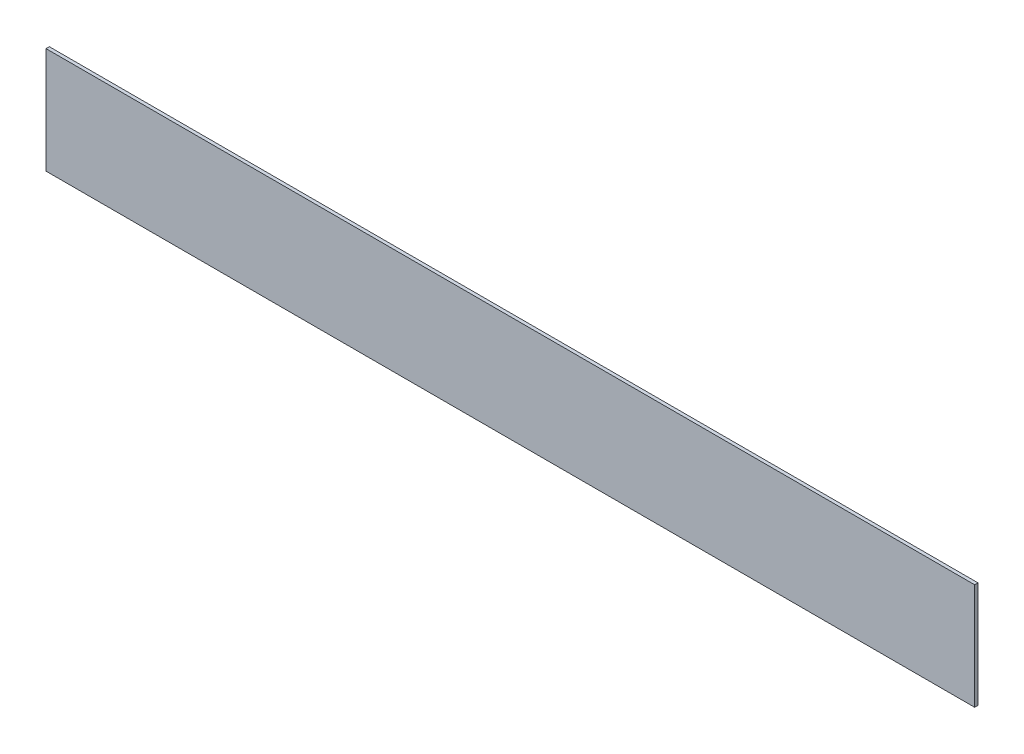
SolidWorks part; units mm, degrees
material "Nylon 101"
ref_plane "Front Plane" through (0, 0, 0) normal (0, 0, 1) x (1, 0, 0)
ref_plane "Top Plane" through (0, 0, 0) normal (0, 1, 0) x (1, 0, 0)
ref_plane "Right Plane" through (0, 0, 0) normal (1, 0, 0) x (0, 0, -1)
sketch "Sketch1" plane through (0, 0, 0) normal (0, 0, 1) x (1, 0, 0)
  line L6 (0, 0) -> (-444.5, 0)
  line L7 (0, 0) -> (0, -50.8)
  line L8 (0, -50.8) -> (-444.5, -50.8)
  line L9 (-444.5, 0) -> (-444.5, -50.8)
  dimension "D1" = 50.8
  dimension "D2" = 444.5
extrude "Boss-Extrude1" add sketch "Sketch1" along normal blind 1.5875
ref_plane "Plane1" through (0, -25.4, 0) normal (0, 1, 0) x (1, 0, 0)
